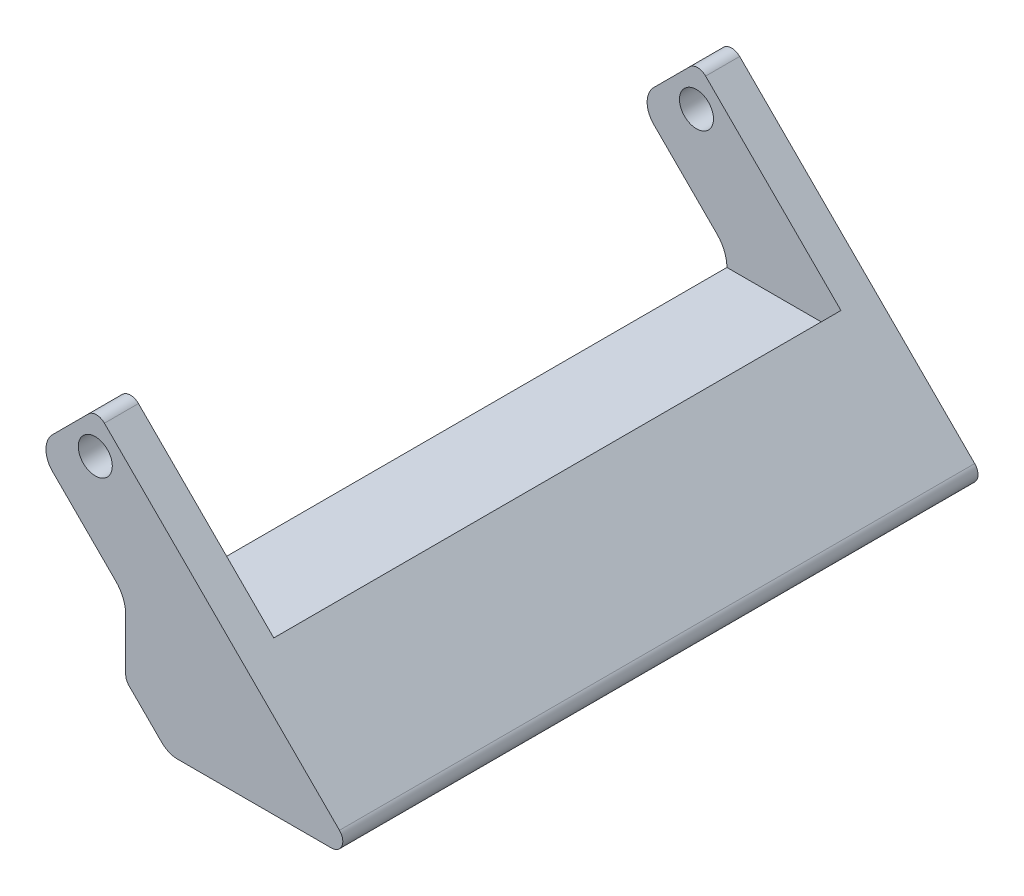
SolidWorks part; units mm, degrees
material "1060-H12"
ref_plane "Front Plane" through (0, 0, 0) normal (0, 0, 1) x (1, 0, 0)
ref_plane "Top Plane" through (0, 0, 0) normal (0, 1, 0) x (1, 0, 0)
ref_plane "Right Plane" through (0, 0, 0) normal (1, 0, 0) x (0, 0, -1)
sketch "Sketch1" plane through (0, 0, 0) normal (0, 0, 1) x (1, 0, 0)
  line L0 (30.0967, -21) -> (76.9648, -21)
  line L1 (3.6822, -19.5) -> (18.5462, -19.5)
  line L2 (-9.1152, 9.3685) -> (-1.6411, 1.8944)
  line L3 (2.6015, -0.934) -> (2.9274, -0.6081)
  line L4 (2.9274, 0.8061) -> (0.8061, 2.9274)
  line L5 (-0.6081, 2.9274) -> (-1.6411, 1.8944)
  line L6 (-1.6411, 1.8944) -> (-3.7625, -0.2269)
  line L7 (-3.7625, -3.0553) -> (1.8035, -8.6213)
  line L8 (2.6822, -10.7426) -> (2.6822, -18.5)
  line L9 (2.6015, -2.3482) -> (18.8997, -18.6464)
  line L10 (2.6015, -0.934) -> (1.8944, -1.6411)
  line L11 (2.6015, -2.3482) -> (1.8944, -1.6411)
  line L12 (2.9274, -0.6081) -> (3.6345, 0.099)
  line L13 (2.9274, 0.8061) -> (3.6345, 0.099)
  circle A0 centre (0, 0) radius 1.5
  circle A1 centre (30.0967, 0.35) radius 21.35
  arc A3 (0.8061, 2.9274) -> (-0.6081, 2.9274) centre (0.099, 2.2203) ccw
  arc A4 (2.6822, -18.5) -> (3.6822, -19.5) centre (3.6822, -18.5) ccw
  arc A6 (-3.7625, -0.2269) -> (-3.7625, -3.0553) centre (-2.3482, -1.6411) ccw
  arc A7 (18.5462, -19.5) -> (18.8997, -18.6464) centre (18.5462, -19) ccw
  arc A8 (1.8035, -8.6213) -> (2.6822, -10.7426) centre (-0.3178, -10.7426) cw
  point P10 (15, -14.7467)
  point P13 (0, 0)
  point P23 (2.6822, -19.5)
  point P26 (1.8944, -1.6411)
  point P33 (2.6822, -9.5)
  point P36 (0, 0)
  dimension "D1" = 3
  dimension "D4" = 42.7
  dimension "D13" = 1
  dimension "D14" = 2
  dimension "D15" = 0.5
  dimension "D16" = 3
  dimension "D2" = 21
  dimension "D3" = 1.5
  dimension "D5" = 45
  dimension "D6" = 15
  dimension "D7" = 2.5
  dimension "D8" = 2.5
  dimension "D9" = 10
  dimension "D10" = 5
  dimension "D11" = 2.64
extrude "Boss-Extrude1" add sketch "Sketch1" along normal blind 3
sketch "Sketch2" plane through (0, 0, 3) normal (0, 0, 1) x (1, 0, 0)
  line L0 (1.8944, -1.6411) -> (18.8997, -18.6464) construction
  line L1 (3.6822, -19.5) -> (18.5462, -19.5) construction
  line L2 (2.6822, -10.7426) -> (2.6822, -18.5) construction
  line L3 (1.8944, -1.6411) -> (18.8997, -18.6464)
  line L4 (3.6822, -19.5) -> (18.5462, -19.5)
  line L5 (2.6822, -10.7426) -> (2.6822, -18.5)
  line L6 (2.6822, -10.7426) -> (10.9959, -10.7426)
  arc A0 (18.5462, -19.5) -> (18.8997, -18.6464) centre (18.5462, -19) ccw construction
  arc A1 (2.6822, -18.5) -> (3.6822, -19.5) centre (3.6822, -18.5) ccw construction
  arc A2 (18.5462, -19.5) -> (18.8997, -18.6464) centre (18.5462, -19) ccw
  arc A3 (2.6822, -18.5) -> (3.6822, -19.5) centre (3.6822, -18.5) ccw
  line M4 (2.6822, -10.7426) -> (2.6822, -18.5)
  arc M5 (2.6822, -18.5) -> (3.6822, -19.5) centre (3.6822, -18.5) ccw
  line M6 (3.6822, -19.5) -> (18.5462, -19.5)
  arc M7 (18.5462, -19.5) -> (18.8997, -18.6464) centre (18.5462, -19) ccw
  line M8 (18.8997, -18.6464) -> (1.8944, -1.6411)
extrude "Boss-Extrude2" add sketch "Sketch2" along normal blind 25 contours L6 M4 M5 M6 M7 M8
mirror "Mirror1" about plane through (0, 0, 28) normal (0, 0, 1) of "Boss-Extrude1", "Boss-Extrude2"
sketch "Sketch3" plane through (2.6822, 0, 0) normal (-1, 0, 0) x (0, 0, 1)
  line L0 (0, -15.7426) -> (56, -15.7426)
  line L1 (0, -10.7426) -> (0, -18.5) construction
  line L2 (56, -10.7426) -> (56, -18.5) construction
  line L3 (53, -10.7426) -> (3, -10.7426) construction
  dimension "D1" = 5
ref_plane "Plane1" through (-6.5302, -6.5302, 0) normal (-0.7071, -0.7071, 0) x (0, 0, 1)
sketch "Sketch6" plane through (-6.5302, -6.5302, 0) normal (-0.7071, -0.7071, 0) x (0, 0, 1)
  line L1 (56, -13.0283) -> (0, -13.0283)
  line L2 (56, -13.0283) -> (56, -22.1438)
  line L3 (56, -22.1438) -> (0, -22.1438)
  line L4 (0, -13.0283) -> (0, -22.1438)
extrude "Cut-Extrude1" cut sketch "Sketch6" along normal through all
fillet "Fillet1" radius 2 1 edges at (6.4396, -19.5, 28)
fillet "Fillet2" radius 1 1 edges at (2.6822, -15.7426, 28)
sketch "Sketch9" plane through (0.1266, 0.1266, 0) normal (0.7071, 0.7071, 0) x (0, 0, -1)
  line L0 (-56, -2.5) -> (-53, -2.5)
  line L1 (-53, -2.5) -> (-53, -15.3715)
  line L2 (-53, -15.3715) -> (-3, -15.3715)
  line L3 (-3, -15.3715) -> (-3, -2.5)
  line L4 (-3, -2.5) -> (0, -2.5)
  line L5 (0, -2.5) -> (0, -26.5491)
  line L6 (0, -26.5491) -> (-56, -26.5491)
  line L7 (-56, -26.5491) -> (-56, -2.5)
  point P14 (0, 0)
extrude "Boss-Extrude4" add sketch "Sketch9" along normal up to surface (2.4609 mm away) up to face at (2.2203, 1.5132, 1.5)
sketch "Sketch10" plane through (0, 0, 0) normal (0, 0, -1) x (-1, 0, 0)
  line L0 (-20.6398, -16.9063) -> (-18.0462, -19.5)
  line L1 (-7.268, -19.5) -> (-18.5462, -19.5) construction
  line L2 (-18.0462, -19.5) -> (-23.2335, -19.5)
  line L3 (-23.2335, -19.5) -> (-20.6398, -16.9063)
extrude "Boss-Extrude5" add sketch "Sketch10" against normal up to surface (56 mm away) up to face at (1.5, 0, 56)
fillet "Fillet3" radius 1 1 edges at (23.2335, -19.5, 28)
